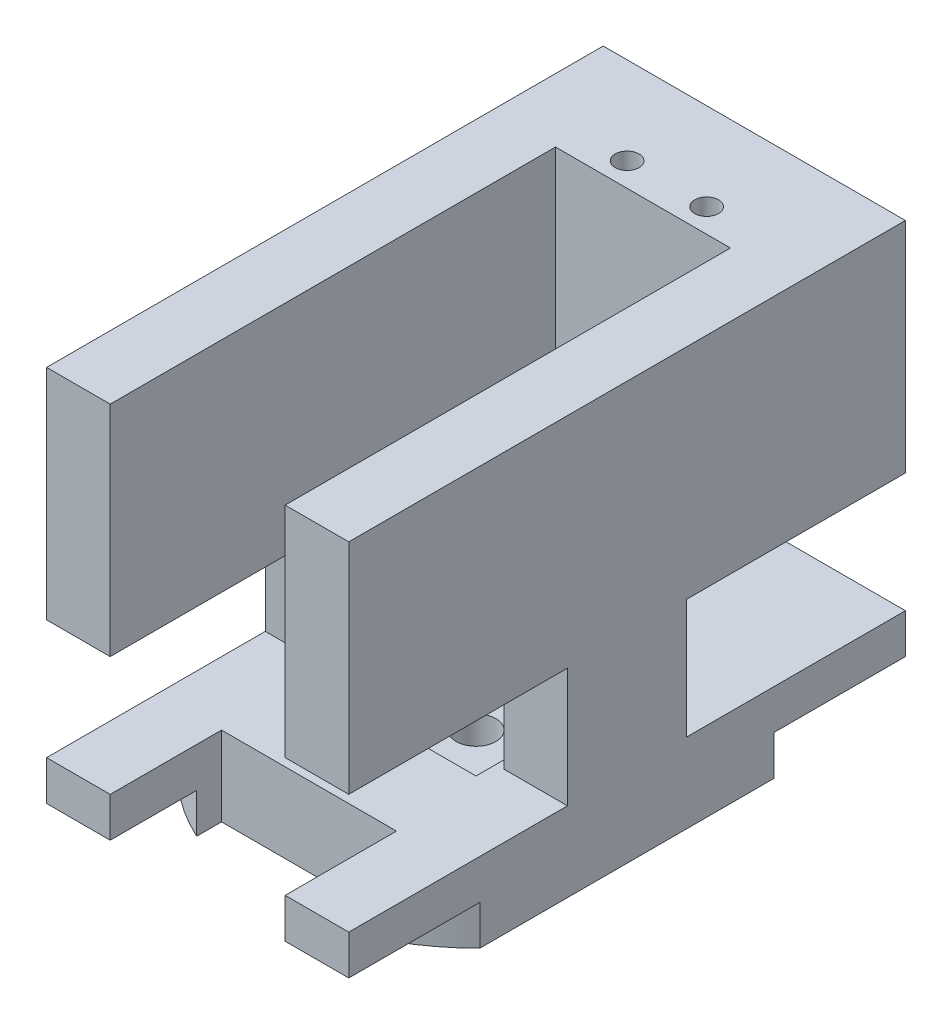
SolidWorks part; units mm, degrees
ref_plane "Front Plane" through (0, 0, 0) normal (0, 0, 1) x (1, 0, 0)
ref_plane "Top Plane" through (0, 0, 0) normal (0, 1, 0) x (1, 0, 0)
ref_plane "Right Plane" through (0, 0, 0) normal (1, 0, 0) x (0, 0, -1)
sketch "Sketch1" plane through (0, 0, 0) normal (0, 1, 0) x (1, 0, 0)
  line L0 (0, 74.7873) -> (0, -69.1899) construction
  line L1 (-45, 35) -> (45, 35)
  line L2 (-45, 35) -> (-45, -35)
  line L3 (-45, -35) -> (45, -35)
  line L4 (45, 35) -> (45, -35)
  line L5 (-45, 35) -> (45, -35) construction
  line L6 (-45, -35) -> (45, 35) construction
  line L12 (-36, -21) -> (-14, 21) construction
  line L13 (-120.0494, 0) -> (109.3545, 0) construction
  line L14 (45, 35) -> (-45, -35) construction
  line L24 (-10, 10) -> (10, -10) construction
  line L25 (-10, -10) -> (10, 10) construction
  point P0 (0, 0)
  point P6 (-25, 0)
  point P35 (0, 0)
  dimension "D1" = 90
  dimension "D2" = 70
  dimension "D5" = 0
  dimension "D12" = 25
  dimension "D13" = 20
  dimension "D14" = 20
extrude "Boss-Extrude1" add sketch "Sketch1" along normal blind 12.5
sketch "Sketch3" plane through (0, 0, 0) normal (0, -1, 0) x (1, 0, 0)
  line L0 (-45, -35) -> (-45, 35) construction
  line L1 (-45, 7.5) -> (45, 7.5)
  line L2 (-45, 7.5) -> (-45, -7.5)
  line L3 (-45, -7.5) -> (45, -7.5)
  line L4 (45, 7.5) -> (45, -7.5)
  line L5 (45, 35) -> (45, -35) construction
  line L6 (-45, 35) -> (45, 35) construction
  line L7 (-36, -21) -> (-36, 21) construction
  line L8 (-45, 7.5) -> (-36, 7.5)
  line L9 (-45, 7.5) -> (-45, -7.5)
  line L10 (-45, -7.5) -> (-36, -7.5)
  line L11 (-36, 7.5) -> (-36, -7.5)
  line L12 (-14, 21) -> (-14, -21) construction
  line L13 (-14, 7.5) -> (14, 7.5)
  line L14 (-14, 7.5) -> (-14, -7.5)
  line L15 (-14, -7.5) -> (14, -7.5)
  line L16 (14, 7.5) -> (14, -7.5)
  line L17 (14, -21) -> (14, 21) construction
  line L18 (36, 21) -> (36, -21) construction
  line L19 (36, 7.5) -> (45, 7.5)
  line L20 (36, 7.5) -> (36, -7.5)
  line L21 (36, -7.5) -> (45, -7.5)
  line L22 (45, 7.5) -> (45, -7.5)
  dimension "D1" = 15
  dimension "D2" = 27.5
extrude "Boss-Extrude2" add sketch "Sketch3" along normal blind 15 contours L14 L1 L11 L3 | L20 L1 L16 L3
sketch "Sketch4" plane through (0, 12.5, 0) normal (0, 1, 0) x (1, 0, 0)
  line L1 (-11, 21) -> (11, 21)
  line L2 (-11, 21) -> (-11, -21)
  line L3 (-11, -21) -> (11, -21)
  line L4 (11, 21) -> (11, -21)
  line L5 (-11, 21) -> (11, -21) construction
  line L6 (-11, -21) -> (11, 21) construction
  circle A0 centre (-5, 24) radius 1.25
  circle A1 centre (5, 24) radius 1.25
  circle A2 centre (5, -24) radius 1.25
  circle A3 centre (-5, -24) radius 1.25
  point P0 (0, 0)
  dimension "D5" = 2.5
  dimension "D6" = 2.5
  dimension "D9" = 2.5
  dimension "D10" = 2.5
  dimension "D1" = 22
  dimension "D2" = 42
  dimension "D3" = 24
  dimension "D4" = 24
  dimension "D7" = 10
  dimension "D8" = 6
extrude "Cut-Extrude1" cut sketch "Sketch4" against normal through all
sketch "Sketch7" plane through (0, -15, 0) normal (0, -1, 0) x (1, 0, 0)
  line L0 (-45, 35) -> (45, 35) construction
  line L1 (-45, 35) -> (45, 35)
  line L2 (-45, 35) -> (-45, -35)
  line L3 (-45, -35) -> (45, -35)
  line L4 (45, 35) -> (45, -35)
  line L5 (-45, 7.5) -> (-45, 35) construction
  line L7 (-10, 10) -> (10, 10)
  line L8 (-10, 10) -> (-10, -10)
  line L9 (-10, -10) -> (10, -10)
  line L10 (10, 10) -> (10, -10)
  line L11 (-10, 10) -> (10, -10) construction
  line L12 (-10, -10) -> (10, 10) construction
  point P9 (0, 0)
extrude "Boss-Extrude3" add sketch "Sketch7" along normal blind 5
sketch "Sketch8" plane through (0, -20, 0) normal (0, -1, 0) x (1, 0, 0)
  circle A0 centre (0, 0) radius 26.5144
  circle A1 centre (0, 0) radius 2.5
  dimension "D1" = 5
extrude "Boss-Extrude4" add sketch "Sketch8" along normal blind 5
sketch "Sketch12" plane through (0, 12.5, 0) normal (0, 1, 0) x (1, 0, 0)
  line L0 (-45, -35) -> (45, -35) construction
  line L1 (-11, -21) -> (11, -21)
  line L2 (-11, -21) -> (-11, -35)
  line L3 (-11, -35) -> (11, -35)
  line L4 (11, -21) -> (11, -35)
  dimension "D1" = 22
extrude "Cut-Extrude3" cut sketch "Sketch12" against normal through all
sketch "Sketch16" plane through (0, 12.5, 0) normal (0, 1, 0) x (1, 0, 0)
  line L0 (-45, -35) -> (-11, -35) construction
  line L1 (-45, 35) -> (-19, 35)
  line L2 (-45, 35) -> (-45, -35)
  line L3 (-45, -35) -> (-19, -35)
  line L4 (-19, 35) -> (-19, -35)
  line L5 (11, -35) -> (45, -35) construction
  line L6 (45, 35) -> (19, 35)
  line L7 (45, 35) -> (45, -35)
  line L8 (45, -35) -> (19, -35)
  line L9 (19, 35) -> (19, -35)
  dimension "D1" = 26
  dimension "D2" = 26
extrude "Cut-Extrude5" cut sketch "Sketch16" against normal through all
sketch "Sketch17" plane through (0, 12.5, 0) normal (0, 1, 0) x (1, 0, 0)
  line L0 (-11, -35) -> (-11, 21)
  line L1 (-19, 35) -> (19, 35)
  line L2 (-19, 35) -> (-19, -35)
  line L3 (-19, -35) -> (19, -35)
  line L4 (19, 35) -> (19, -35)
  line L5 (-11, 21) -> (11, 21)
  line L6 (11, 21) -> (11, -35)
  line L7 (11, -35) -> (19, -35)
  line L8 (-11, -35) -> (-19, -35)
  circle A0 centre (-5, 24) radius 1.25
  circle A1 centre (5, 24) radius 1.25
  line M1 (-19, 35) -> (-19, -35)
  line M2 (-19, -35) -> (-11, -35)
  line M3 (-11, -35) -> (-11, 21)
  line M4 (-11, 21) -> (11, 21)
  line M5 (11, 21) -> (11, -35)
  line M6 (11, -35) -> (19, -35)
  line M7 (19, -35) -> (19, 35)
  line M8 (19, 35) -> (-19, 35)
  circle M9 centre (5, 24) radius 1.25
  circle M10 centre (-5, 24) radius 1.25
extrude "Boss-Extrude5" add sketch "Sketch17" along normal blind 15 contours M8 M1 M2 M3 M4 M5 M6 M7 M9 M10
sketch "Sketch18" plane through (0, 27.5, 0) normal (0, 1, 0) x (1, 0, 0)
  circle A0 centre (-5, 24) radius 1.5
  circle A1 centre (5, 24) radius 1.5
  dimension "D1" = 3
  dimension "D2" = 3
extrude "Cut-Extrude6" cut sketch "Sketch18" against normal blind 30
